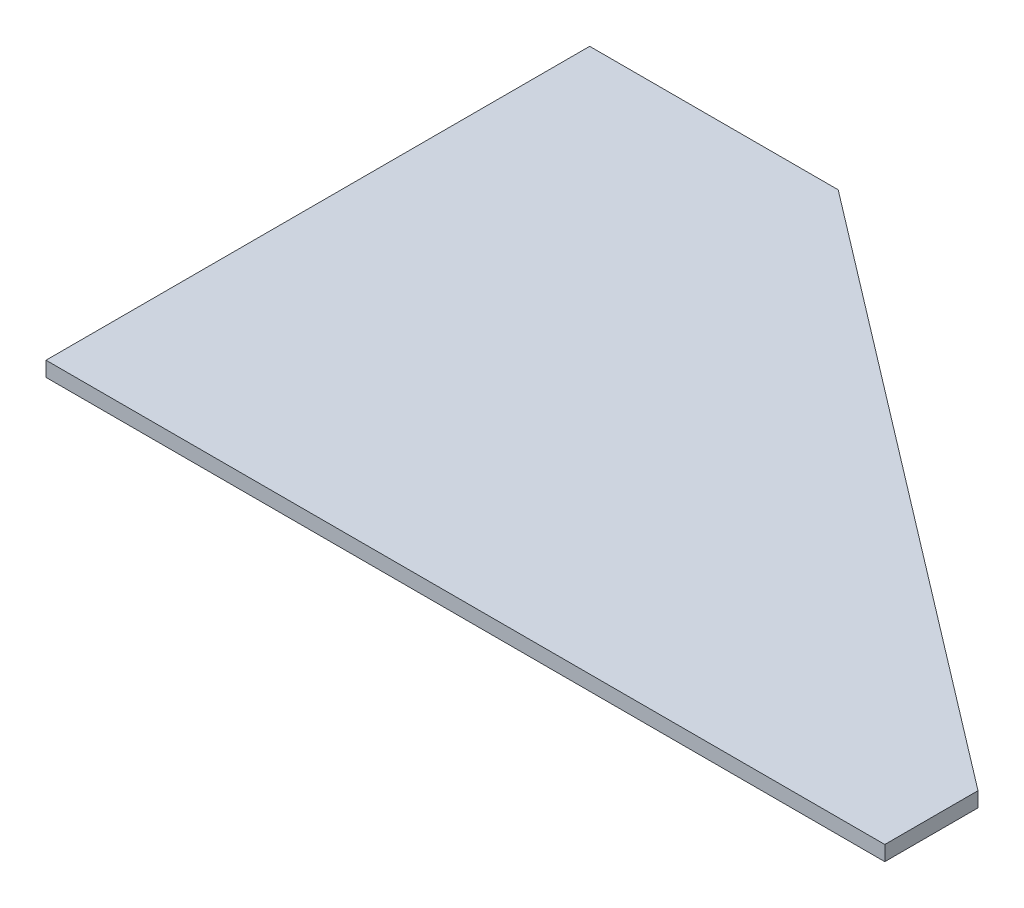
SolidWorks part; units mm, degrees
material "Thornel VCB-20 Carbon Cloth"
ref_plane "Front Plane" through (0, 0, 0) normal (0, 0, 1) x (1, 0, 0)
ref_plane "Top Plane" through (0, 0, 0) normal (0, 1, 0) x (1, 0, 0)
ref_plane "Right Plane" through (0, 0, 0) normal (1, 0, 0) x (0, 0, -1)
sketch "Sketch1" plane through (0, 0, 0) normal (0, 1, 0) x (1, 0, 0)
  line L0 (-135, 175) -> (-135, 0)
  line L1 (-135, 0) -> (135, 0)
  line L2 (135, 0) -> (135, 30)
  line L3 (135, 30) -> (-55, 175)
  line L4 (-55, 175) -> (-135, 175)
  dimension "D1" = 270
  dimension "D2" = 175
  dimension "D3" = 80
  dimension "D4" = 30
extrude "Boss-Extrude1" add sketch "Sketch1" along normal mid plane 4.8
